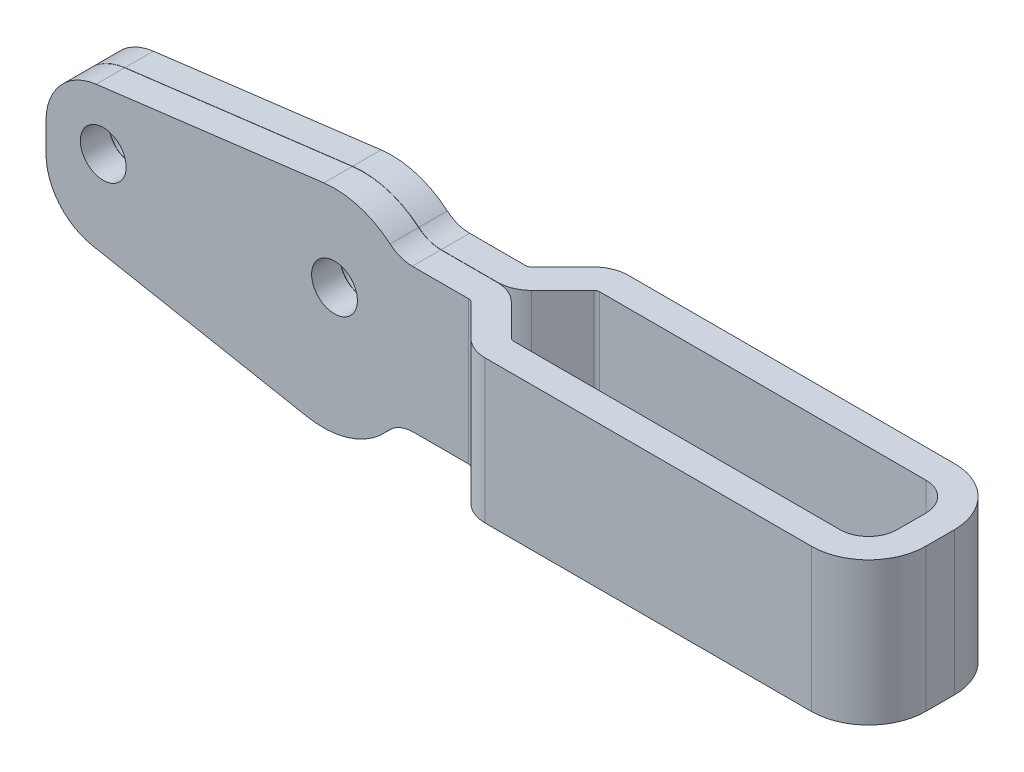
SolidWorks part; units mm, degrees
ref_plane "Plane1" through (0, 0, 0) normal (0, 0, 1) x (1, 0, 0)
ref_plane "Plane2" through (0, 0, 0) normal (0, 1, 0) x (-1, 0, 0)
ref_plane "Plane3" through (0, 0, 0) normal (1, 0, 0) x (0, 0, -1)
sketch "Sketch1" plane through (0, 0, 0) normal (0, 0, 1) x (1, 0, 0)
  line L0 (0, 0) -> (96.012, 0)
  line L1 (0, 0) -> (0, 15.875)
  line L2 (96.012, 15.875) -> (0, 15.875)
  line L3 (96.012, 15.875) -> (96.012, 0)
  dimension "D1" = 96.012
  dimension "D2" = 15.875
extrude "Base-Extrude" add sketch "Sketch1" along normal mid plane 15.875
sketch "Sketch3" plane through (0, 15.875, 0) normal (0, 1, 0) x (-1, 0, 0)
  line L0 (-53.213, -4.7625) -> (-92.837, -4.7625)
  line L1 (0, 0) -> (-68.2806, 0) construction
  line L2 (-92.837, 4.7625) -> (-53.213, 4.7625)
  line L3 (-92.837, 4.7625) -> (-92.837, -4.7625)
  line L4 (-96.012, -7.9375) -> (0, -7.9375) construction
  line L5 (-96.012, 7.9375) -> (-96.012, -7.9375) construction
  line L6 (-96.012, 7.9375) -> (0, 7.9375) construction
  line L7 (2.1181, -3.175) -> (-47.1354, -3.175)
  line L8 (-53.213, -4.7625) -> (-48.4505, 0)
  line L9 (-48.4505, 0) -> (-53.213, 4.7625)
  line L10 (2.1181, 3.175) -> (-47.1354, 3.175)
  line L11 (-47.1354, -3.175) -> (-55.8484, -11.888)
  line L12 (-47.1354, 3.175) -> (-55.8484, 11.888)
  line L13 (-55.8484, -11.888) -> (2.1181, -11.888)
  line L14 (-55.8484, 11.888) -> (2.1181, 11.888)
  line L15 (2.1181, -11.888) -> (2.1181, -3.175)
  line L16 (2.1181, 11.888) -> (2.1181, 3.175)
  dimension "D1" = 39.624
  dimension "D2" = 3.175
  dimension "D3" = 3.175
  dimension "D4" = 3.175
  dimension "D5" = 45
  dimension "D6" = 3.175
  dimension "D7" = 3.175
extrude "Cut-Extrude1" cut sketch "Sketch3" against normal through all
fillet "Fillet5" radius 0.635 4 edges at (53.213, 7.9375, -4.7625) (53.213, 7.9375, 4.7625) (47.1354, 7.9375, 3.175) (47.1354, 7.9375, -3.175)
fillet "Fillet6" radius 3.81 2 edges at (51.8979, 7.9375, 7.9375) (51.8979, 7.9375, -7.9375)
fillet "Fillet7" radius 3.175 2 edges at (92.837, 7.9375, -4.7625) (92.837, 7.9375, 4.7625)
fillet "Fillet8" radius 6.35 2 edges at (96.012, 7.9375, 7.9375) (96.012, 7.9375, -7.9375)
fillet "Fillet9" radius 6.35 1 edges at (0, 15.875, 0)
fillet "Fillet10" radius 6.35 1 edges at (0, 0, 0)
sketch "Sketch6" plane through (0, 0, 3.175) normal (0, 0, 1) x (1, 0, 0)
  line L0 (6.35, 15.875) -> (46.8723, 15.875) construction
  line L1 (7.6318, 9.525) -> (42.545, 9.525) construction
  line L2 (0, 6.35) -> (0, 9.525) construction
  line L3 (38.862, 36.1043) -> (38.862, -14.5143) construction
  line L4 (96.012, 15.875) -> (96.012, 0) construction
  line L5 (5.5641, 15.8262) -> (30.8252, 18.9768)
  line L7 (29.4622, 19.05) -> (53.4108, 19.05) construction
  line L8 (28.2376, -4.572) -> (39.9397, -4.572) construction
  line L9 (5.1654, 0.1115) -> (28.9491, -4.4048)
  line L10 (0, 6.35) -> (0, 9.525)
  arc A0 (6.35, 15.875) -> (0, 9.525) centre (6.35, 9.525) ccw construction
  arc A2 (40.249, 4.7558) -> (30.8252, 18.9768) centre (32.004, 9.525) ccw
  arc A3 (5.5641, 15.8262) -> (0, 9.525) centre (6.35, 9.525) ccw
  arc A4 (40.249, 4.7558) -> (28.9491, -4.4048) centre (30.7261, 4.953) cw
  arc A5 (0, 6.35) -> (6.35, 0) centre (6.35, 6.35) ccw construction
  arc A6 (0, 6.35) -> (5.1654, 0.1115) centre (6.35, 6.35) ccw
  dimension "D1" = 19.05
  dimension "D4" = 24.4161
  dimension "D5" = 9.525
  dimension "D2" = 57.15
  dimension "D3" = 25.654
  dimension "D6" = 23.622
  dimension "D7" = 6.35
extrude "Boss-Extrude3" add sketch "Sketch6" against normal up to surface (6.35 mm away)
fillet "Fillet11" radius 3.81 2 edges at (38.862, 0, 0) (39.1035, 15.875, 0)
sketch "Sketch7" plane through (0, 0, 3.175) normal (0, 0, 1) x (1, 0, 0)
  circle A0 centre (6.35, 9.525) radius 2.54
  circle A1 centre (32.004, 9.525) radius 2.54
  arc A2 (5.5641, 15.8262) -> (0, 9.525) centre (6.35, 9.525) ccw construction
  arc A3 (38.1732, 16.7821) -> (30.8252, 18.9768) centre (32.004, 9.525) ccw construction
  dimension "D1" = 5.08
extrude "Cut-Extrude5" cut sketch "Sketch7" against normal through all
sketch "Sketch8" plane through (0, 15.875, 0) normal (0, 1, 0) x (-1, 0, 0)
  line L0 (0, 0) -> (-59.8442, 0) construction
  line L1 (-53.476, -4.7625) -> (-53.476, 5.9871) construction
  line L2 (3.175, 0.0127) -> (-53.476, 0.0127)
  line L3 (3.175, 0.0127) -> (3.175, -0.0127)
  line L4 (-53.476, -0.0127) -> (3.175, -0.0127)
  line L5 (-53.476, -0.0127) -> (-53.476, 0.0127)
  line L6 (0, 3.175) -> (0, -3.175) construction
  dimension "D1" = 3.175
  dimension "D2" = 0.0127
  dimension "D3" = 0.0254
extrude "Cut-Extrude6" cut sketch "Sketch8" against normal through all and the other way through all
fillet "Fillet12" radius 3.81 1 edges at (48.4632, 7.9375, 0.0127)
fillet "Fillet13" radius 3.81 1 edges at (48.4632, 7.9375, -0.0127)
equation "\"D2@Sketch3\" = \"D3@Sketch3\""
equation "\"D4@Sketch3\" = \"D2@Sketch3\""
equation "\"D6@Sketch3\" = \"D2@Sketch3\""
equation "\"D7@Sketch3\" = \"D2@Sketch3\""
